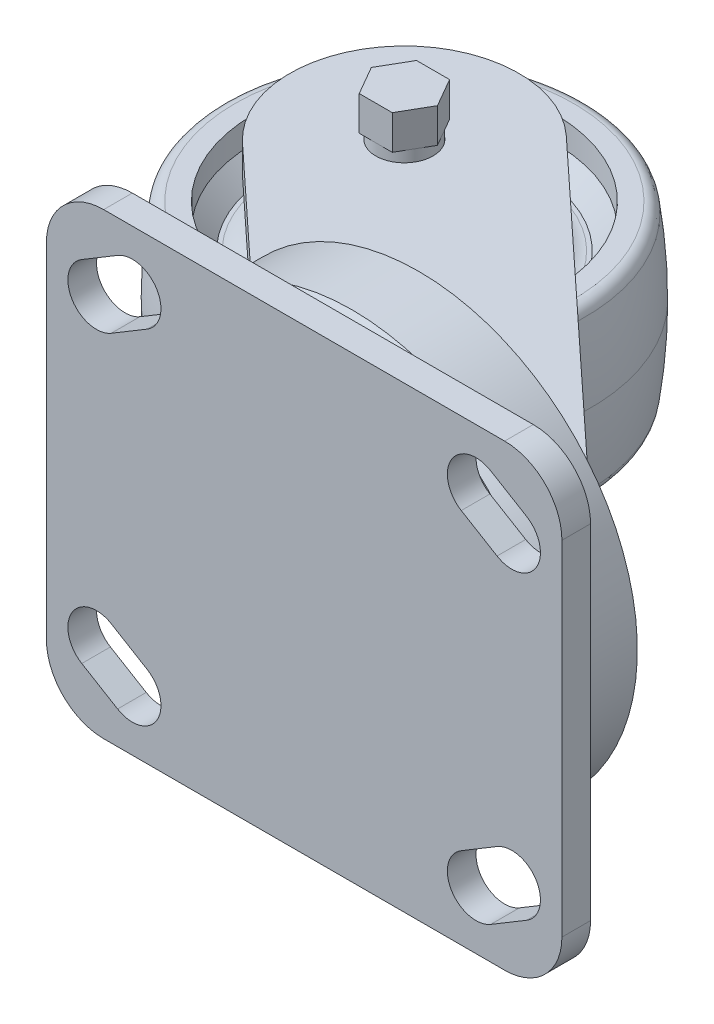
SolidWorks part; units mm, degrees
ref_plane "Front" through (0, 0, 0) normal (0, 0, 1) x (1, 0, 0)
ref_plane "Top" through (0, 0, 0) normal (0, 1, 0) x (1, 0, 0)
ref_plane "Right" through (0, 0, 0) normal (1, 0, 0) x (0, 0, -1)
sketch "Sketch1" plane through (0, 0, 0) normal (0, 0, 1) x (1, 0, 0)
  line L0 (0, 22.225) -> (0, 0) construction
  line L1 (-22.225, 0) -> (0, 0) construction
  line L2 (0, 0) -> (0, -23.8125)
  line L3 (0, -23.8125) -> (22.225, -23.8125)
  line L4 (22.225, -23.8125) -> (22.225, -15.875)
  line L5 (28.575, -9.525) -> (29.4556, -9.525)
  line L6 (33.401, -13.4704) -> (33.401, -19.05)
  line L7 (33.401, -19.05) -> (39.751, -19.05)
  line L8 (44.45, 0) -> (44.45, -9.525) construction
  line L9 (41.275, 0) -> (0, 0)
  line L10 (44.45, -9.525) -> (44.45, -24.5745) construction
  line L11 (88.9105, -24.5745) -> (-0.0105, -24.5745) construction
  line L12 (0, -24.5745) -> (0, -23.8125) construction
  line L13 (-0.0105, -24.5745) -> (0, -24.5745) construction
  line L14 (4.1472, -30.9245) -> (84.7528, -30.9245) construction
  line L15 (29.4556, -9.525) -> (33.401, -13.4704)
  arc A0 (41.275, 0) -> (39.751, -19.05) centre (-78.5495, 0) cw
  circle A1 centre (44.45, 0) radius 50.8 construction
  arc A2 (28.575, -9.525) -> (22.225, -15.875) centre (28.575, -15.875) ccw
  dimension "D2" = 9.525
  dimension "Plate Width" = 101.6
  dimension "D7" = 6.35
  dimension "D1" = 0.762
  dimension "Wheel Dia" = 82.55
  dimension "Wheel Width" = 38.1
  dimension "D3" = 1.524
  dimension "D4" = 47.625
  dimension "D6" = 44.45
  dimension "D8" = 135
  dimension "Swivel Lead" = 44.45
  dimension "Leg Thickness" = 6.35
  dimension "Wheel Thickness" = 6.35
revolve "Revolve1" add sketch "Sketch1" angle 360 about L0
fillet "Fillet4" radius 2.54 1 edges at (-39.751, -19.05, 0)
chamfer "Chamfer1" distance 1.524 angle 45 1 edges at (-22.225, -23.8125, 0)
ref_plane "Plane1" through (0, -24.5745, 0) normal (0, -1, 0) x (1, 0, 0)
sketch "Sketch3" plane through (0, -24.5745, 0) normal (0, -1, 0) x (1, 0, 0)
  line L0 (-17.2835, 18.613) -> (7.1218, 41.275)
  line L1 (7.1218, 47.625) -> (81.7782, 47.625) construction
  line L2 (81.7782, 41.275) -> (17.2835, -18.613)
  line L3 (44.45, 47.625) -> (44.45, 60.325) construction
  line L4 (81.7782, 41.275) -> (7.1218, 41.275)
  line L5 (81.7782, 41.275) -> (81.7782, 47.625) construction
  line L6 (7.1218, 47.625) -> (7.1218, 41.275) construction
  line L7 (44.45, 0) -> (44.45, 47.625) construction
  line L8 (-12.7, 66.675) -> (101.6, 66.675) construction
  line L9 (-12.7, 66.675) -> (-12.7, 60.325) construction
  line L10 (-12.7, 60.325) -> (101.6, 60.325) construction
  line L11 (101.6, 66.675) -> (101.6, 60.325) construction
  line L14 (0, 0) -> (44.45, 41.275) construction
  arc A0 (-17.2835, 18.613) -> (17.2835, -18.613) centre (0, 0) ccw
  circle A2 centre (0, 0) radius 41.275 construction
  point P11 (44.45, 47.625)
  point P18 (44.45, 60.325)
  dimension "D1" = 50.8
  dimension "D3" = 12.7
  dimension "Overall Height" = 107.95
  dimension "Plate Thickness" = 6.35
  dimension "Plate Length" = 114.3
extrude "Extrude1" add sketch "Sketch3" along normal blind 6.35 separate body
sketch "Sketch7" plane through (0, 0, 0) normal (0, 1, 0) x (1, 0, 0)
  line L1 (-12.7, -66.675) -> (101.6, -66.675)
  line L2 (-12.7, -66.675) -> (-12.7, -60.325)
  line L3 (-12.7, -60.325) -> (101.6, -60.325)
  line L4 (101.6, -66.675) -> (101.6, -60.325)
extrude "Extrude2" add sketch "Sketch7" against normal blind 50.8 separate body
sketch "Sketch20" plane through (0, 0, 41.275) normal (0, 0, 1) x (1, 0, 0)
  line L0 (-6.35, 0) -> (95.25, 0)
  arc A1 (-6.35, 0) -> (95.25, 0) centre (44.45, 0) ccw
  dimension "D1" = 50.8
extrude "Extrude8" add sketch "Sketch20" along normal up to vertex (6.35 mm away) up to point (44.45, -24.5745, 47.625)
sketch "Sketch24" plane through (0, 0, 41.275) normal (0, 0, -1) x (-1, 0, 0)
  line L0 (-57.15, 0) -> (-31.75, 0)
  line L1 (6.35, 0) -> (-95.25, 0) construction
  arc A0 (-57.15, 0) -> (-31.75, 0) centre (-44.45, 0) ccw
  dimension "D1" = 25.4
extrude "Extrude10" add sketch "Sketch24" along normal blind 3.175
sketch "Sketch8" plane through (0, 0, 47.625) normal (0, 0, 1) x (1, 0, 0)
  line L0 (-6.35, 0) -> (12.7, 0)
  line L1 (76.2, 0) -> (95.25, 0)
  arc A0 (12.7, 0) -> (76.2, 0) centre (44.45, 0) ccw
  arc A1 (-6.35, 0) -> (95.25, 0) centre (44.45, 0) ccw
  circle A4 centre (44.45, 0) radius 50.8 construction
  dimension "D1" = 19.05
extrude "Extrude3" add sketch "Sketch8" along normal offset from surface (11.176 mm away) 1.524 up to face at (44.45, -25.4, 60.325)
chamfer "Chamfer2" distance 5.08 angle 45 1 edges at (44.45, -50.8, 58.801)
sketch "Sketch9" plane through (0, 0, 60.325) normal (0, 0, -1) x (-1, 0, 0)
  line L0 (6.35, 0) -> (-12.7, 0) construction
  line L1 (-44.45, -31.75) -> (-44.45, -25.4) construction
  line L3 (-69.85, 0) -> (-50.8, 0)
  line L4 (-38.1, 0) -> (-19.05, 0)
  arc A0 (-69.85, 0) -> (-19.05, 0) centre (-44.45, 0) ccw
  arc A1 (-50.8, 0) -> (-38.1, 0) centre (-44.45, 0) ccw
  arc A3 (-76.2, 0) -> (-12.7, 0) centre (-44.45, 0) ccw construction
  arc A4 (-76.2, 0) -> (-12.7, 0) centre (-44.45, 0) ccw construction
  dimension "D1" = 6.35
extrude "Extrude4" add sketch "Sketch9" along normal offset from surface (11.43 mm away) 1.27 up to face at (76.2, 0, 47.625)
chamfer "Chamfer3" distance 5.08 angle 45 1 edges
sketch "Sketch10" plane through (0, 0, 66.675) normal (0, 0, 1) x (1, 0, 0)
  line L0 (44.45, 0) -> (44.45, -50.8) construction
  line L1 (1.6795, -27.8924) -> (9.617, -32.6549)
  line L2 (101.6, -50.8) -> (-12.7, -50.8) construction
  line L3 (-4.8545, -38.7826) -> (3.083, -43.5451)
  line L4 (85.817, -43.5451) -> (93.7545, -38.7826)
  line L5 (0, 0) -> (44.45, 0) construction
  line L6 (41.275, 0) -> (-41.275, 0) construction
  line L7 (87.2205, -27.8924) -> (79.283, -32.6549)
  line L8 (5.6483, -30.2737) -> (-0.8858, -41.1638) construction
  line L9 (83.2517, -30.2737) -> (89.7858, -41.1638) construction
  arc A0 (3.083, -43.5451) -> (9.617, -32.6549) centre (6.35, -38.1) ccw
  arc A1 (1.6795, -27.8924) -> (-4.8545, -38.7826) centre (-1.5875, -33.3375) ccw
  arc A2 (87.2205, -27.8924) -> (93.7545, -38.7826) centre (90.4875, -33.3375) cw
  arc A3 (79.283, -32.6549) -> (85.817, -43.5451) centre (82.55, -38.1) ccw
  point P7 (2.3812, -35.7187)
  point P25 (86.5188, -35.7187)
  dimension "D1" = 6.35
  dimension "D2" = 76.2
  dimension "D3" = 76.2
  dimension "Hole1 Width" = 66.675
  dimension "Hole1 Length" = 92.075
extrude "Cut-Extrude1" cut sketch "Sketch10" against normal up to next (6.35 mm away)
fillet "Fillet1" radius 12.7 2 edges at (101.6, -50.8, 63.5) (-12.7, -50.8, 63.5)
sketch "Sketch11" plane through (0, -24.5745, 0) normal (0, 1, 0) x (-1, 0, 0)
  line L0 (0, 27.94) -> (0, -27.94) construction
  line L1 (27.94, 0) -> (-27.94, 0) construction
  circle A0 centre (0, 0) radius 6.35
  dimension "Bolt Size" = 12.7
extrude "Cut-Extrude2" cut sketch "Sketch11" against normal through all and the other way through all
sketch "Sketch12" plane through (0, 0, 0) normal (0, 1, 0) x (-1, 0, 0)
  line L0 (0, 6.3246) -> (0, 6.35) construction
  circle A0 centre (0, 0) radius 6.3246
  circle A2 centre (0, 0) radius 6.35 construction
  circle A3 centre (0, 0) radius 6.35 construction
  dimension "D1" = 0.0254
extrude "Extrude5" add sketch "Sketch12" against normal offset from surface (33.4645 mm away) 2.54 separate body up to face at (6.35, -30.9245, 0) offset beyond the face yes
sketch "Sketch13" plane through (0, -33.4645, 0) normal (0, -1, 0) x (1, 0, 0)
  line L1 (3.6662, 6.35) -> (-3.6662, 6.35)
  line L2 (-3.6662, 6.35) -> (-7.3323, 0)
  line L3 (-7.3323, 0) -> (-3.6662, -6.35)
  line L4 (-3.6662, -6.35) -> (3.6662, -6.35)
  line L5 (3.6662, -6.35) -> (7.3323, 0)
  line L6 (7.3323, 0) -> (3.6662, 6.35)
  circle A0 centre (0, 0) radius 6.35 construction
  circle A1 centre (0, 0) radius 6.35 construction
  circle A2 centre (0, 0) radius 6.3246 construction
extrude "Extrude6" add sketch "Sketch13" along normal blind 7.62
mirror "Mirror1" about plane through (0, 0, 0) normal (0, 1, 0) of bodies 115 116 117 119 108
split line "Split Line1"
sketch "Sketch25" plane through (0, 0, 66.675) normal (0, 0, 1) x (1, 0, 0)
  line L0 (-0.8858, 41.1638) -> (5.6483, 30.2737) construction
  line L1 (-4.8545, 38.7826) -> (3.083, 43.5451) construction
  line L2 (9.617, 32.6549) -> (1.6795, 27.8924) construction
  line L3 (83.2517, 30.2737) -> (89.7858, 41.1638) construction
  line L4 (87.2205, 27.8924) -> (79.283, 32.6549) construction
  line L5 (85.817, 43.5451) -> (93.7545, 38.7826) construction
  point P12 (2.3812, 35.7188)
  point P13 (86.5188, 35.7188)
sketch "Sketch26" plane through (0, 0, 41.275) normal (0, 0, -1) x (-1, 0, 0)
  circle A0 centre (-44.45, 0) radius 48.4739
  circle A1 centre (-44.45, 0) radius 50.8 construction
  circle A2 centre (-44.45, 0) radius 50.8
extrude "Cut-Extrude3" cut sketch "Sketch26" against normal blind 17.78
equation "\"D4@Sketch1\"=\"Wheel Width@Sketch1\"+.375"
equation "\"Plate Width@Extrude2\"=\"Plate Width@Sketch1\"/2"
equation "\"D2@Extrude1\"=\"Leg Thickness@Sketch1\""
